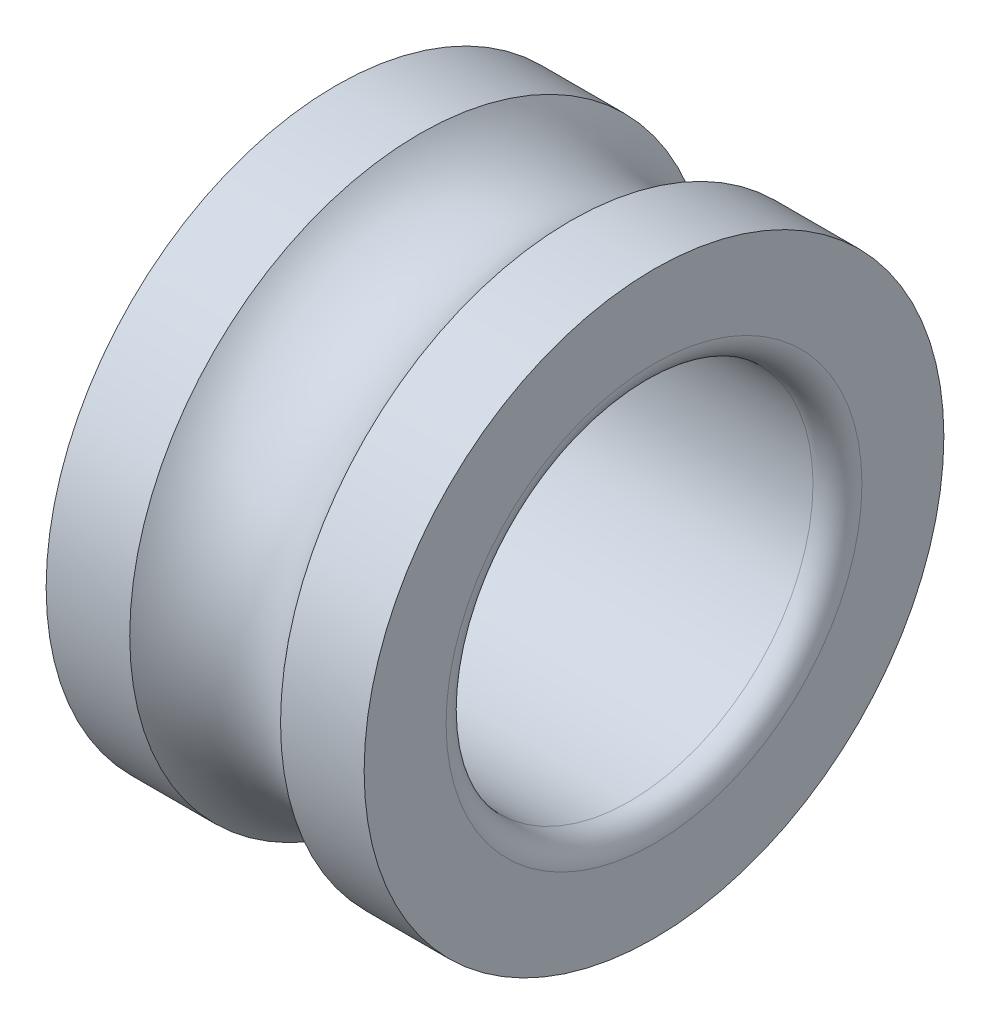
SolidWorks part; units mm, degrees
ref_plane "Front Plane" through (0, 0, 0) normal (0, 0, 1) x (1, 0, 0)
ref_plane "Top Plane" through (0, 0, 0) normal (0, 1, 0) x (1, 0, 0)
ref_plane "Right Plane" through (0, 0, 0) normal (1, 0, 0) x (0, 0, -1)
ref_plane "Plane1"
sketch "Sketch1" plane through (0, 0, 0) normal (0, 0, 1) x (1, 0, 0)
  line L0 (1, 7.5) -> (12, 7.5)
  line L1 (13, 8.5) -> (13, 11.85)
  line L2 (13, 11.85) -> (9.5827, 11.85)
  line L3 (3.4173, 11.85) -> (0, 11.85)
  line L4 (0, 11.85) -> (0, 8.5)
  line L5 (50, 0) -> (-50, 0) construction
  arc A0 (0, 8.5) -> (1, 7.5) centre (1, 8.5) ccw
  arc A1 (12, 7.5) -> (13, 8.5) centre (12, 8.5) ccw
  arc A2 (3.4173, 11.85) -> (9.5827, 11.85) centre (6.5, 14.35) ccw
revolve "Revolução1" add sketch "Sketch1" angle 360 about L5
